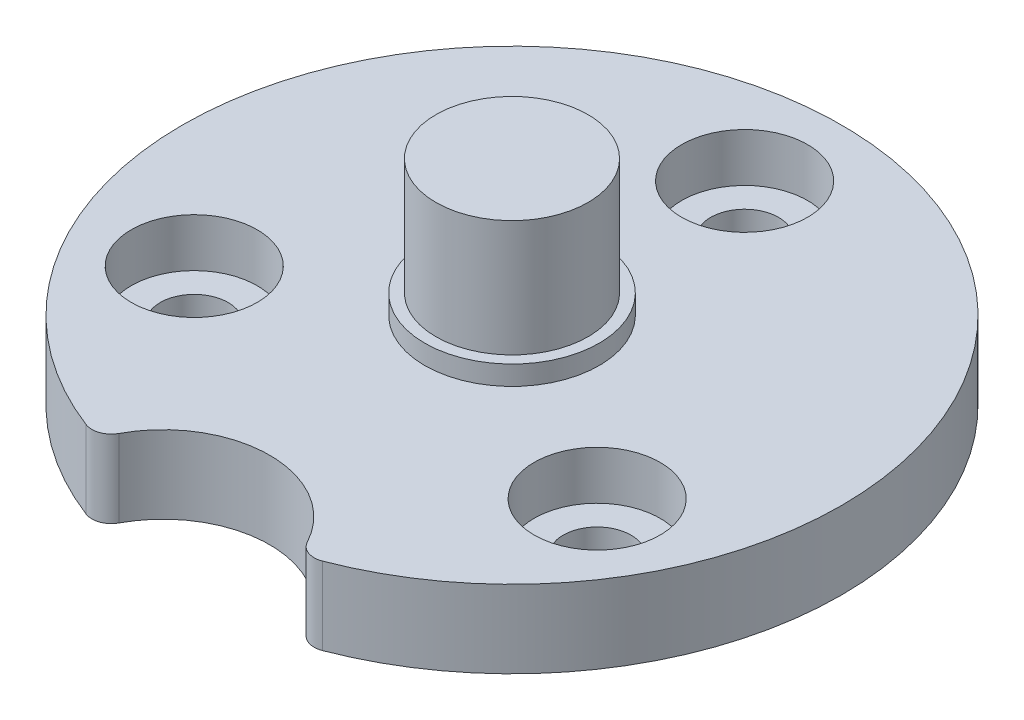
SolidWorks part; units mm, degrees
ref_plane "Front Plane" through (0, 0, 0) normal (0, 0, 1) x (1, 0, 0)
ref_plane "Top Plane" through (0, 0, 0) normal (0, 1, 0) x (1, 0, 0)
ref_plane "Right Plane" through (0, 0, 0) normal (1, 0, 0) x (0, 0, -1)
sketch "Sketch1" plane through (0, 0, 0) normal (0, 1, 0) x (1, 0, 0)
  line L0 (0, 0) -> (0, 15.6071) construction
  circle A0 centre (0, 0) radius 17
  circle A1 centre (0, 12) radius 1.75
  circle A2 centre (10.3923, -6) radius 1.75
  circle A3 centre (-10.3923, -6) radius 1.75
  point P12 (0, 0)
  dimension "D1" = 34
  dimension "D3" = 3.5
  dimension "D2" = 12
  dimension "D4" = 3
extrude "Boss-Extrude1" add sketch "Sketch1" along normal blind 4
sketch "Sketch2" plane through (0, 4, 0) normal (0, 1, 0) x (1, 0, 0)
  circle A0 centre (0, 12) radius 3.25
  circle A1 centre (10.3923, -6) radius 3.25
  circle A2 centre (-10.3923, -6) radius 3.25
  point P9 (0, 0)
  dimension "D1" = 6.5
  dimension "D2" = 3
extrude "Cut-Extrude1" cut sketch "Sketch2" against normal blind 2.5
sketch "Sketch3" plane through (0, 4, 0) normal (0, 1, 0) x (1, 0, 0)
  circle A0 centre (0, 0) radius 4.5
  dimension "D1" = 9
extrude "Boss-Extrude2" add sketch "Sketch3" along normal blind 1
sketch "Sketch4" plane through (0, 5, 0) normal (0, 1, 0) x (1, 0, 0)
  circle A0 centre (0, 0) radius 3.925
  dimension "D1" = 7.85
extrude "Boss-Extrude3" add sketch "Sketch4" along normal blind 6
sketch "Sketch5" plane through (0, 4, 0) normal (0, 1, 0) x (1, 0, 0)
  circle A0 centre (0, -18) radius 5.5
  dimension "D1" = 11
  dimension "D2" = 18
extrude "Cut-Extrude2" cut sketch "Sketch5" against normal up to next
fillet "Fillet1" radius 1 2 edges at (-5.1928, 2, 16.1875) (5.1928, 2, 16.1875)
